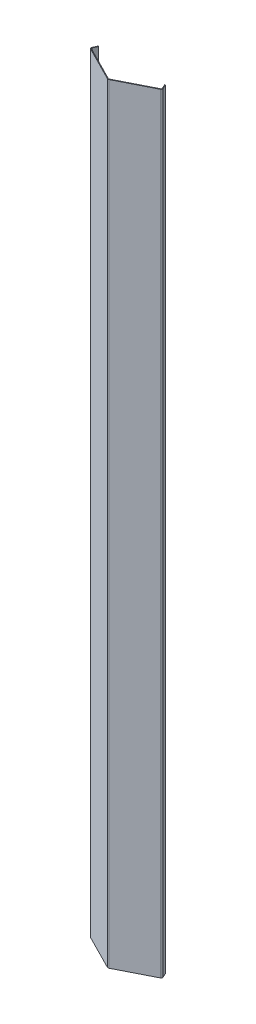
SolidWorks part; units mm, degrees
material "ASTM A36 Steel"
ref_plane "Front Plane" through (0, 0, 0) normal (0, 0, 1) x (1, 0, 0)
ref_plane "Top Plane" through (0, 0, 0) normal (0, 1, 0) x (1, 0, 0)
ref_plane "Right Plane" through (0, 0, 0) normal (1, 0, 0) x (0, 0, -1)
sketch "Sketch1" plane through (0, 0, 0) normal (0, 1, 0) x (1, 0, 0)
  line L3 (319.2222, 134.9653) -> (331.4949, 107.6505)
  line L5 (112.7099, -13.8833) -> (326.8928, 94.6317)
  line L15 (-99.1928, 133.3259) -> (-111.4654, 106.0111)
  line L16 (105.4787, -10.3152) -> (-108.7041, 98.1998)
  line L17 (110.9021, -10.3152) -> (325.085, 98.1998)
  line L18 (315.5736, 133.3259) -> (327.8462, 106.0111)
  line L20 (103.6709, -13.8833) -> (-110.5119, 94.6317)
  line L21 (-102.8414, 134.9653) -> (-115.114, 107.6505)
  line L22 (-102.8414, 134.9653) -> (-99.1928, 133.3259)
  line L23 (319.2222, 134.9653) -> (315.5736, 133.3259)
  arc A0 (331.4949, 107.6505) -> (326.8928, 94.6317) centre (322.3733, 103.5521) cw
  arc A2 (103.6709, -13.8833) -> (112.7099, -13.8833) centre (108.1904, -4.9629) ccw
  arc A6 (-111.4654, 106.0111) -> (-108.7041, 98.1998) centre (-105.9924, 103.5521) ccw
  arc A7 (105.4787, -10.3152) -> (110.9021, -10.3152) centre (108.1904, -4.9629) ccw
  arc A8 (327.8462, 106.0111) -> (325.085, 98.1998) centre (322.3733, 103.5521) cw
  arc A11 (-115.114, 107.6505) -> (-110.5119, 94.6317) centre (-105.9924, 103.5521) ccw
  point P7 (335.4063, 98.945)
  point P31 (-119.0254, 98.945)
  dimension "D2" = 10
  dimension "D1" = 4
extrude "Boss-Extrude2" add sketch "Sketch1" along normal blind 4830
